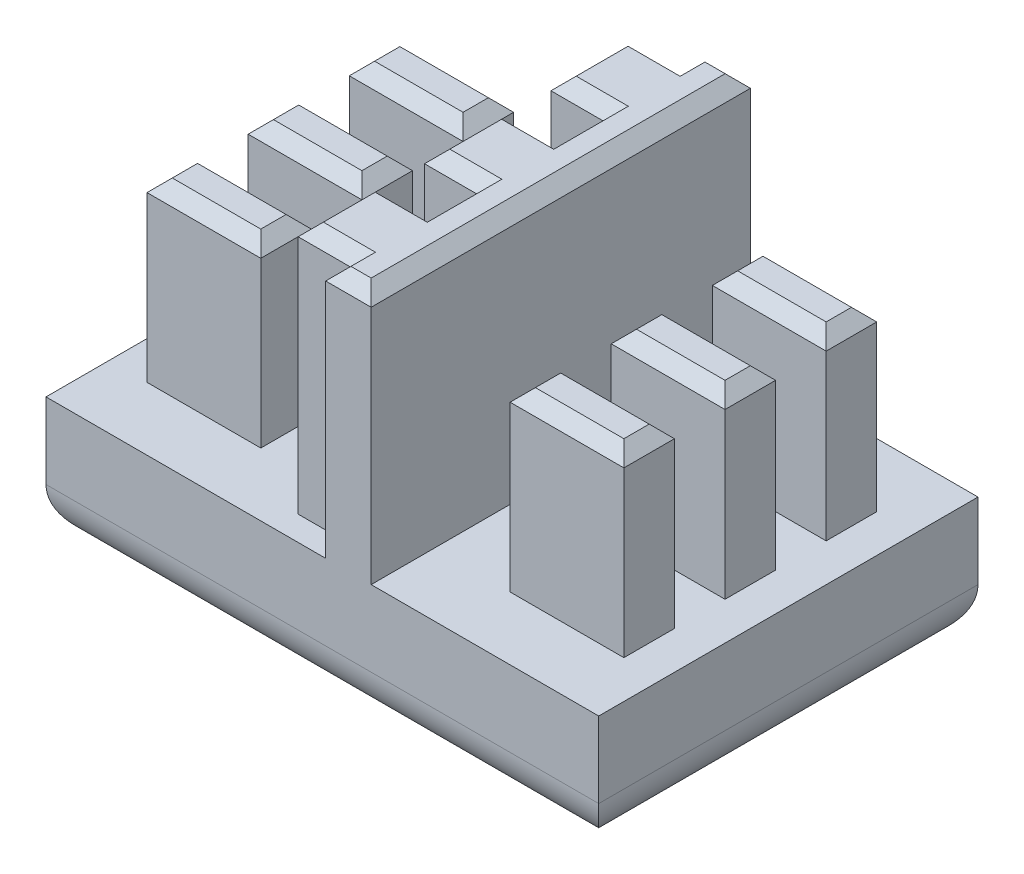
SolidWorks part; units mm, degrees
material "PEI"
ref_plane "前视基准面" through (0, 0, 0) normal (0, 0, 1) x (1, 0, 0)
ref_plane "上视基准面" through (0, 0, 0) normal (0, 1, 0) x (1, 0, 0)
ref_plane "右视基准面" through (0, 0, 0) normal (1, 0, 0) x (0, 0, -1)
sketch "草图1" plane through (0, 0, 0) normal (0, 1, 0) x (1, 0, 0)
  line L0 (-0.13, 3.475) -> (-0.13, 1.525)
  line L1 (-9.69, 5) -> (-5.19, 5)
  line L2 (-9.69, 5) -> (-9.69, 3)
  line L3 (-9.69, 3) -> (-5.19, 3)
  line L4 (-5.19, 5) -> (-5.19, 3)
  line L5 (-9.69, 1) -> (-5.19, 1)
  line L6 (-9.69, 1) -> (-9.69, -1)
  line L7 (-9.69, -1) -> (-5.19, -1)
  line L8 (-5.19, 1) -> (-5.19, -1)
  line L9 (-9.69, -3) -> (-5.19, -3)
  line L10 (-9.69, -3) -> (-9.69, -5)
  line L11 (-9.69, -5) -> (-5.19, -5)
  line L12 (-5.19, -3) -> (-5.19, -5)
  line L13 (4.67, 5) -> (9.17, 5)
  line L14 (4.67, 5) -> (4.67, 3)
  line L15 (4.67, 3) -> (9.17, 3)
  line L16 (9.17, 5) -> (9.17, 3)
  line L17 (4.67, -1) -> (9.17, -1)
  line L18 (4.67, -1) -> (4.67, 1)
  line L19 (4.67, 1) -> (9.17, 1)
  line L20 (9.17, -1) -> (9.17, 1)
  line L21 (-0.13, 7.505) -> (1.67, 7.505)
  line L22 (9.17, -3) -> (4.67, -3)
  line L23 (9.17, -3) -> (9.17, -5)
  line L24 (9.17, -5) -> (4.67, -5)
  line L25 (4.67, -3) -> (4.67, -5)
  line L26 (-0.13, 7.505) -> (-0.13, 6.525)
  line L27 (-0.13, -7.495) -> (1.67, -7.495)
  line L28 (1.67, 7.505) -> (1.67, -7.495)
  line L29 (-2.19, 6.525) -> (-0.13, 6.525)
  line L30 (-2.19, 6.525) -> (-2.19, 3.475)
  line L31 (-2.19, 3.475) -> (-0.13, 3.475)
  line L33 (-2.19, 1.525) -> (-0.13, 1.525)
  line L34 (-2.19, 1.525) -> (-2.19, -1.525)
  line L35 (-2.19, -1.525) -> (-0.13, -1.525)
  line L37 (-2.19, -3.475) -> (-0.13, -3.475)
  line L38 (-2.19, -3.475) -> (-2.19, -6.525)
  line L39 (-2.19, -6.525) -> (-0.13, -6.525)
  line L41 (-0.13, -1.525) -> (-0.13, -3.475)
  line L42 (-0.13, -6.525) -> (-0.13, -7.495)
  dimension "D1" = 2
  dimension "D2" = 2
  dimension "D3" = 2
  dimension "D4" = 4.5
  dimension "D5" = 4.5
  dimension "D6" = 2
  dimension "D7" = 2
  dimension "D8" = 9.86
  dimension "D9" = 3
  dimension "D10" = 1
  dimension "D11" = 2.06
  dimension "D12" = 1.8
  dimension "D13" = 15
  dimension "D14" = 1.95
  dimension "D15" = 1.95
  dimension "D16" = 3.05
  dimension "D17" = 3.05
  dimension "D18" = 3.05
  dimension "D19" = 0.98
  dimension "D20" = 0.13
  dimension "D21" = 1.525
extrude "凸台-拉伸1" add sketch "草图1" along normal blind 7
sketch "草图2" plane through (0, 7, 0) normal (0, 1, 0) x (1, 0, 0)
  line L0 (-0.13, 7.505) -> (-0.13, 6.525)
  line L1 (-0.13, 6.525) -> (-2.19, 6.525)
  line L2 (-2.19, 6.525) -> (-2.19, 3.475)
  line L3 (-2.19, 3.475) -> (-0.13, 3.475)
  line L4 (-0.13, 3.475) -> (-0.13, 1.525)
  line L5 (-0.13, 1.525) -> (-2.19, 1.525)
  line L6 (-2.19, 1.525) -> (-2.19, -1.525)
  line L7 (-2.19, -1.525) -> (-0.13, -1.525)
  line L8 (-0.13, -1.525) -> (-0.13, -3.475)
  line L9 (-0.13, -3.475) -> (-2.19, -3.475)
  line L10 (-2.19, -3.475) -> (-2.19, -6.525)
  line L11 (-2.19, -6.525) -> (-0.13, -6.525)
  line L12 (-0.13, -6.525) -> (-0.13, -7.495)
  line L13 (-0.13, -7.495) -> (1.67, -7.495)
  line L14 (1.67, -7.495) -> (1.67, 7.505)
  line L17 (1.67, 7.505) -> (-0.13, 7.505)
extrude "凸台-拉伸2" add sketch "草图2" along normal blind 3
sketch "草图3" plane through (0, 0, 0) normal (0, -1, 0) x (1, 0, 0)
  line L0 (-0.13, 7.495) -> (1.67, 7.495) construction
  line L1 (-11.19, 7.495) -> (10.67, 7.495)
  line L2 (-11.19, 7.495) -> (-11.19, -7.505)
  line L3 (-11.19, -7.505) -> (10.67, -7.505)
  line L4 (10.67, 7.495) -> (10.67, -7.505)
  line L5 (1.67, -7.505) -> (-0.13, -7.505) construction
  line L6 (-9.69, -1) -> (-9.69, 1) construction
  line L7 (9.17, 1) -> (9.17, -1) construction
  dimension "D1" = 0
  dimension "D2" = 0
  dimension "D3" = 1.5
  dimension "D4" = 1.5
extrude "凸台-拉伸3" add sketch "草图3" along normal blind 5
fillet "圆角1" radius 2 4 edges at (-0.26, -5, -7.505) (-11.19, -5, -0.005) (10.67, -5, -0.005) (-0.26, -5, 7.495)
chamfer "倒角1" distance 0.5 angle 45 40 edges at (1.67, 10, -0.005) (0.77, 10, 7.495) (-0.13, 10, 7.01) (-1.16, 10, 6.525) (-2.19, 10, 5) (-1.16, 10, 3.475) (-0.13, 10, 2.5) (-1.16, 10, 1.525) (-2.19, 10, 0) (-1.16, 10, -1.525) (-0.13, 10, -2.5) (-1.16, 10, -3.475) (-2.19, 10, -5) (-1.16, 10, -6.525) (-0.13, 10, -7.015) (0.77, 10, -7.505) (-7.44, 7, 3) (-5.19, 7, 4) (-7.44, 7, 5) (-9.69, 7, 4) (-7.44, 7, -1) (-5.19, 7, 0) (-7.44, 7, 1) (-9.69, 7, 0) (-7.44, 7, -5) (-5.19, 7, -4) (-7.44, 7, -3) (-9.69, 7, -4) (6.92, 7, -5) (9.17, 7, -4) (6.92, 7, -3) (4.67, 7, -4) (6.92, 7, 5) (4.67, 7, 4) (6.92, 7, 3) (9.17, 7, 4) (6.92, 7, -1) (9.17, 7, 0) (6.92, 7, 1) (4.67, 7, 0)
